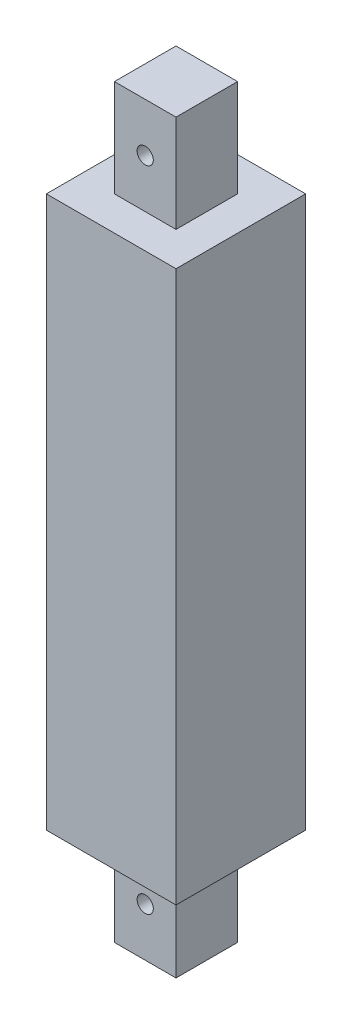
SolidWorks part; units mm, degrees
ref_plane "Front Plane" through (0, 0, 0) normal (0, 0, 1) x (1, 0, 0)
ref_plane "Top Plane" through (0, 0, 0) normal (0, 1, 0) x (1, 0, 0)
ref_plane "Right Plane" through (0, 0, 0) normal (1, 0, 0) x (0, 0, -1)
sketch "Sketch1" plane through (0, 0, 0) normal (0, 1, 0) x (1, 0, 0)
  line L1 (-20, 20) -> (20, 20)
  line L2 (-20, 20) -> (-20, -20)
  line L3 (-20, -20) -> (20, -20)
  line L4 (20, 20) -> (20, -20)
  line L5 (-20, 20) -> (20, -20) construction
  line L6 (-20, -20) -> (20, 20) construction
  point P0 (0, 0)
  dimension "D1" = 40
  dimension "D2" = 40
extrude "Boss-Extrude1" add sketch "Sketch1" along normal blind 170
sketch "Sketch2" plane through (0, 170, 0) normal (0, 1, 0) x (1, 0, 0)
  line L1 (-9.5, 9.5) -> (9.5, 9.5)
  line L2 (-9.5, 9.5) -> (-9.5, -9.5)
  line L3 (-9.5, -9.5) -> (9.5, -9.5)
  line L4 (9.5, 9.5) -> (9.5, -9.5)
  line L5 (-9.5, 9.5) -> (9.5, -9.5) construction
  line L6 (-9.5, -9.5) -> (9.5, 9.5) construction
  point P0 (0, 0)
  dimension "D1" = 19
  dimension "D2" = 19
extrude "Boss-Extrude3" add sketch "Sketch2" along normal blind 30
sketch "Sketch3" plane through (0, 0, 0) normal (0, -1, 0) x (1, 0, 0)
  line L1 (-9.5, 9.5) -> (9.5, 9.5)
  line L2 (-9.5, 9.5) -> (-9.5, -9.5)
  line L3 (-9.5, -9.5) -> (9.5, -9.5)
  line L4 (9.5, 9.5) -> (9.5, -9.5)
  line L5 (-9.5, 9.5) -> (9.5, -9.5) construction
  line L6 (-9.5, -9.5) -> (9.5, 9.5) construction
  point P0 (0, 0)
  dimension "D1" = 19
  dimension "D2" = 19
extrude "Boss-Extrude4" add sketch "Sketch3" along normal blind 30
sketch "Sketch4" plane through (0, 0, -9.5) normal (0, 0, -1) x (-1, 0, 0)
  line L0 (9.5, 0) -> (-9.5, 0) construction
  line L1 (-9.5, -30) -> (-9.5, 0) construction
  line L2 (-9.5, 170) -> (9.5, 170) construction
  line L4 (9.5, 200) -> (9.5, 170) construction
  circle A0 centre (0, -15) radius 2.5
  circle A1 centre (0, 185) radius 2.5
  point P10 (0, 0)
  point P12 (9.5, 265.4096)
  dimension "D1" = 5
  dimension "D4" = 5
  dimension "D2" = 15
  dimension "D3" = 9.5
  dimension "D5" = 15
  dimension "D6" = 9.5
extrude "Cut-Extrude1" cut sketch "Sketch4" against normal blind 19
